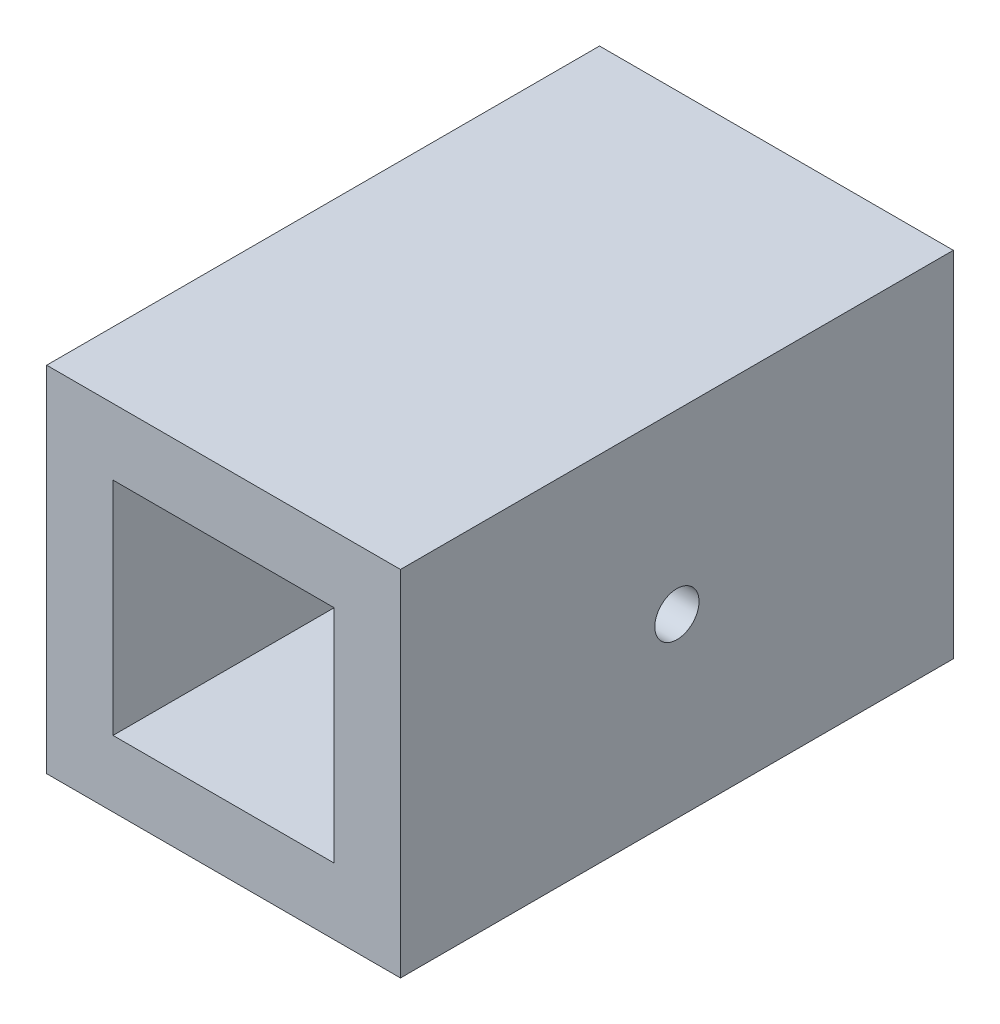
SolidWorks part; units mm, degrees
ref_plane "前视基准面" through (0, 0, 0) normal (0, 0, 1) x (1, 0, 0)
ref_plane "上视基准面" through (0, 0, 0) normal (0, 1, 0) x (1, 0, 0)
ref_plane "右视基准面" through (0, 0, 0) normal (1, 0, 0) x (0, 0, -1)
sketch "草图1" plane through (0, 0, 0) normal (0, 0, 1) x (1, 0, 0)
  line L1 (0, 0) -> (16, 0)
  line L2 (0, 0) -> (0, 16)
  line L3 (0, 16) -> (16, 16)
  line L4 (16, 0) -> (16, 16)
  line L5 (3, 3) -> (13, 3)
  line L6 (3, 3) -> (3, 13)
  line L7 (3, 13) -> (13, 13)
  line L8 (13, 3) -> (13, 13)
  point P5 (3, 3)
  point P10 (0, 0)
  point P11 (0, 0)
  point P12 (0, 0)
  point P13 (0, 0)
  point P14 (0, 0)
  point P15 (0, 0)
  point P16 (0, 0)
  point P17 (0, 0)
  point P18 (0, 0)
  point P19 (0, 0)
  point P20 (0, 0)
  point P21 (0, 0)
  point P22 (0, 0)
  point P23 (0, 0)
  point P24 (0, 0)
  point P25 (0, 0)
extrude "凸台-拉伸1" add sketch "草图1" along normal blind 10
sketch "草图2" plane through (0, 0, 10) normal (0, 0, 1) x (1, 0, 0)
  line L1 (0, 16) -> (16, 16)
  line L2 (0, 16) -> (0, 0)
  line L3 (0, 0) -> (16, 0)
  line L4 (16, 16) -> (16, 0)
extrude "凸台-拉伸2" add sketch "草图2" along normal blind 5
sketch "草图3" plane through (0, 0, 15) normal (0, 0, 1) x (1, 0, 0)
  line L1 (0, 16) -> (16, 16)
  line L2 (0, 16) -> (0, 0)
  line L3 (0, 0) -> (16, 0)
  line L4 (16, 16) -> (16, 0)
  line L5 (3, 13) -> (13, 13)
  line L6 (3, 13) -> (3, 3)
  line L7 (3, 3) -> (13, 3)
  line L8 (13, 13) -> (13, 3)
  point P6 (3, 13)
  point P11 (0, 0)
  point P12 (0, 0)
extrude "凸台-拉伸3" add sketch "草图3" along normal blind 10
sketch "草图4" plane through (16, 0, 0) normal (1, 0, 0) x (0, 0, -1)
  circle A0 centre (-11.5, 6) radius 1
  point P0 (-11.5, 6)
sketch "草图5" plane through (16, 0, 0) normal (1, 0, 0) x (0, 0, -1)
  circle A0 centre (-12.5, 6) radius 1
  point P0 (-12.5, 6)
  point P4 (0, 0)
sketch "草图6" plane through (16, 0, 0) normal (1, 0, 0) x (0, 0, -1)
  circle A0 centre (-12.5, 8) radius 1
  point P0 (-12.5, 8)
extrude "切除-拉伸1" cut sketch "草图6" against normal blind 16
